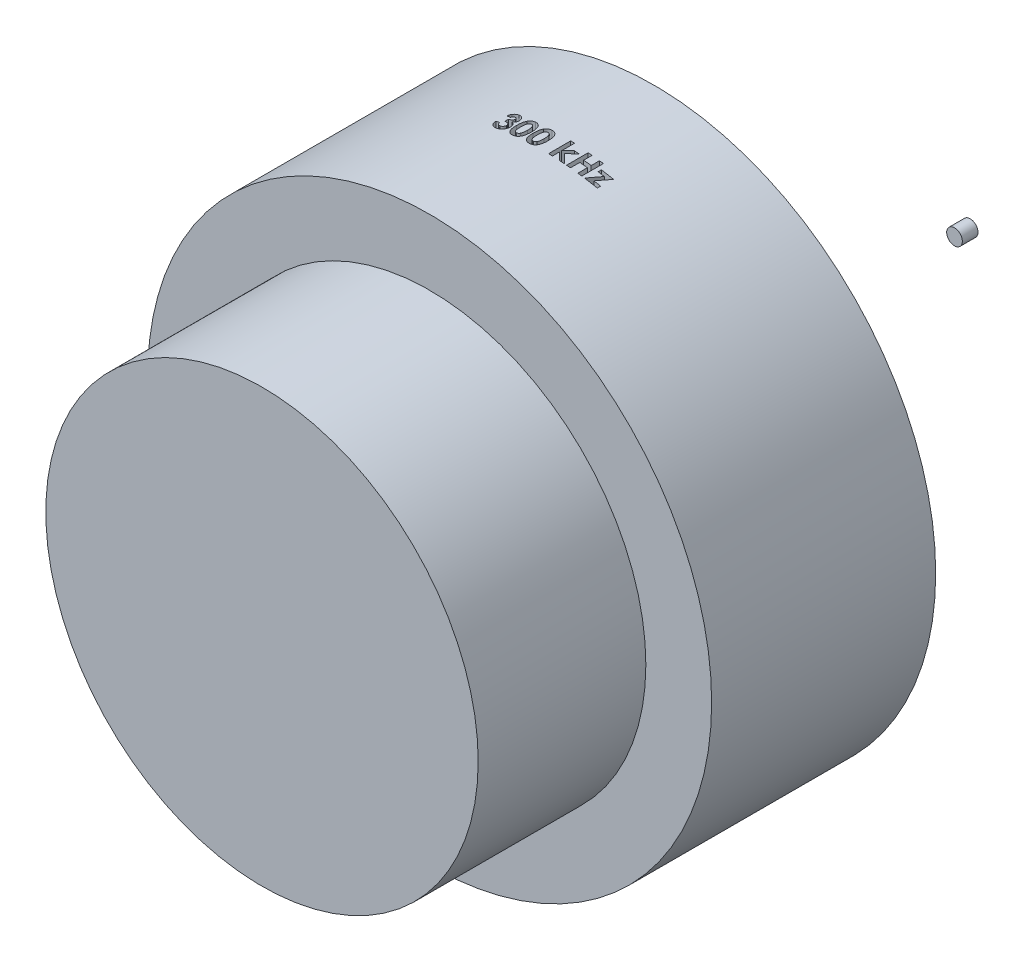
SolidWorks part; units mm, degrees
ref_plane "Front Plane" through (0, 0, 0) normal (0, 0, 1) x (1, 0, 0)
ref_plane "Top Plane" through (0, 0, 0) normal (0, 1, 0) x (1, 0, 0)
ref_plane "Right Plane" through (0, 0, 0) normal (1, 0, 0) x (0, 0, -1)
sketch "Sketch1" plane through (0, 0, 0) normal (1, 0, 0) x (0, 0, -1)
  line L0 (0, 0) -> (21.9023, 0) construction
  line L1 (0, 0) -> (0, 35.052)
  line L2 (0, 35.052) -> (27.178, 35.052)
  line L3 (27.178, 35.052) -> (27.178, 45.72)
  line L4 (27.178, 45.72) -> (63.5, 45.72)
  line L5 (63.5, 45.72) -> (63.5, 0)
  line L6 (63.5, 0) -> (0, 0)
  line L7 (112.268, 0) -> (112.268, 1.27)
  line L8 (112.268, 1.27) -> (114.808, 1.27)
  line L9 (114.808, 1.27) -> (114.808, 0)
  line L10 (112.268, 0) -> (114.808, 0)
  line L11 (0, 0) -> (196.29, 0) construction
  point P10 (113.538, 0)
  dimension "D1" = 1.27
  dimension "D2" = 2.54
  dimension "D3" = 50.038
  dimension "D4" = 45.72
  dimension "D5" = 35.052
  dimension "D6" = 36.322
  dimension "D7" = 63.5
revolve "Revolve1" add sketch "Sketch1" angle 360 about L11
sketch "Sketch2" plane through (0, 0, 0) normal (0, 1, 0) x (1, 0, 0)
  line L0 (-45.72, 45.339) -> (45.72, 45.339) construction
  line L1 (-45.72, 63.5) -> (-45.72, 27.178) construction
  line L2 (45.72, 27.178) -> (45.72, 63.5) construction
  text T0 "<b>300 kHz</b>"
extrude "Cut-Extrude1" cut sketch "Sketch2" against normal blind 12.7 from offset 50.8
